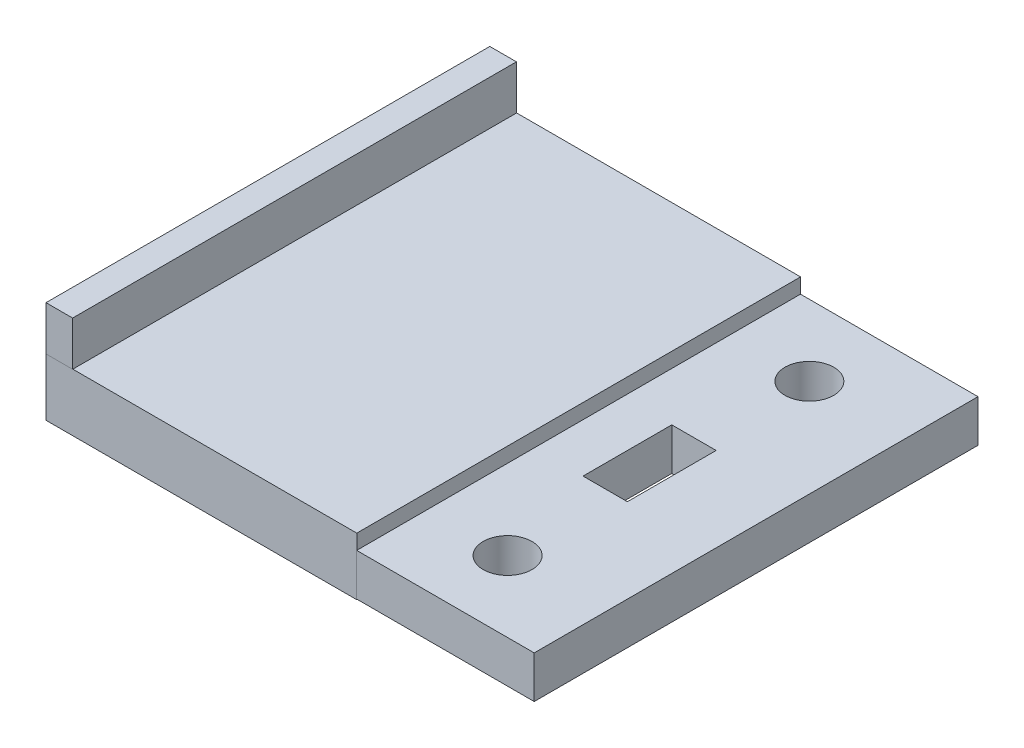
SolidWorks part; units mm, degrees
ref_plane "Plan de face" through (0, 0, 0) normal (0, 0, 1) x (1, 0, 0)
ref_plane "Plan de dessus" through (0, 0, 0) normal (0, 1, 0) x (1, 0, 0)
ref_plane "Plan de droite" through (0, 0, 0) normal (1, 0, 0) x (0, 0, -1)
sketch "Esquisse2" plane through (0, 0, 0) normal (0, 1, 0) x (1, 0, 0)
  line L1 (-12.6282, 10.0321) -> (7.3718, 10.0321)
  line L2 (-12.6282, 10.0321) -> (-12.6282, -39.9679)
  line L3 (-12.6282, -39.9679) -> (7.3718, -39.9679)
  line L4 (7.3718, 10.0321) -> (7.3718, -39.9679)
  line L5 (-12.6282, 10.0321) -> (7.3718, -39.9679) construction
  line L6 (-12.6282, -39.9679) -> (7.3718, 10.0321) construction
  point P0 (-2.6282, -14.9679)
  dimension "D1" = 50
  dimension "D2" = 20
extrude "Boss.-Extru.1" add sketch "Esquisse2" along normal blind 4.75
sketch "Esquisse3" plane through (0, 4.75, 0) normal (0, 1, 0) x (1, 0, 0)
  line L8 (-12.6282, -39.9679) -> (7.3718, -39.9679) construction
  line L11 (7.3718, -39.9679) -> (7.3718, 10.0321) construction
  circle A0 centre (-3.6282, 2.0321) radius 2.75
  circle A1 centre (-3.6282, -31.9679) radius 2.75
  dimension "D1" = 5.5
  dimension "D2" = 5.5
  dimension "D3" = 34
  dimension "D4" = 8
  dimension "D5" = 11
  dimension "D8" = 11
extrude "Enlèv. mat.-Extru.1" cut sketch "Esquisse3" against normal through all
sketch "Esquisse6" plane through (-12.6282, 0, 0) normal (-1, 0, 0) x (0, 0, 1)
  line L1 (39.9583, -0.0683) -> (-10.0417, -0.0683)
  line L2 (39.9583, -0.0683) -> (39.9583, 6.4317)
  line L3 (39.9583, 6.4317) -> (-10.0417, 6.4317)
  line L4 (-10.0417, -0.0683) -> (-10.0417, 6.4317)
  dimension "D1" = 6.5
  dimension "D2" = 50
extrude "Boss.-Extru.2" add sketch "Esquisse6" along normal blind 35
sketch "Esquisse7" plane through (0, 6.4317, 0) normal (0, 1, 0) x (1, 0, 0)
  line L1 (-47.6197, 10.0198) -> (-44.6197, 10.0198)
  line L2 (-47.6197, 10.0198) -> (-47.6197, -39.9802)
  line L3 (-47.6197, -39.9802) -> (-44.6197, -39.9802)
  line L4 (-44.6197, 10.0198) -> (-44.6197, -39.9802)
  dimension "D1" = 3
  dimension "D2" = 50
extrude "Boss.-Extru.3" add sketch "Esquisse7" along normal blind 5
sketch "Esquisse8" plane through (0, 4.75, 0) normal (0, 1, 0) x (1, 0, 0)
  line L0 (7.3718, 10.0321) -> (-12.6282, 10.0321) construction
  line L1 (-7.1282, -9.9679) -> (-2.1282, -9.9679)
  line L2 (-7.1282, -9.9679) -> (-7.1282, -19.9679)
  line L3 (-7.1282, -19.9679) -> (-2.1282, -19.9679)
  line L4 (-2.1282, -9.9679) -> (-2.1282, -19.9679)
  line L5 (-7.1282, -9.9679) -> (-2.1282, -19.9679) construction
  line L6 (-7.1282, -19.9679) -> (-2.1282, -9.9679) construction
  line L10 (-12.6282, 10.0417) -> (-12.6282, -39.9583) construction
  point P0 (-4.6282, -14.9679)
  dimension "D1" = 5
  dimension "D2" = 10
  dimension "D3" = 20
  dimension "D4" = 5.5
extrude "Enlèv. mat.-Extru.2" cut sketch "Esquisse8" against normal blind 5.5
